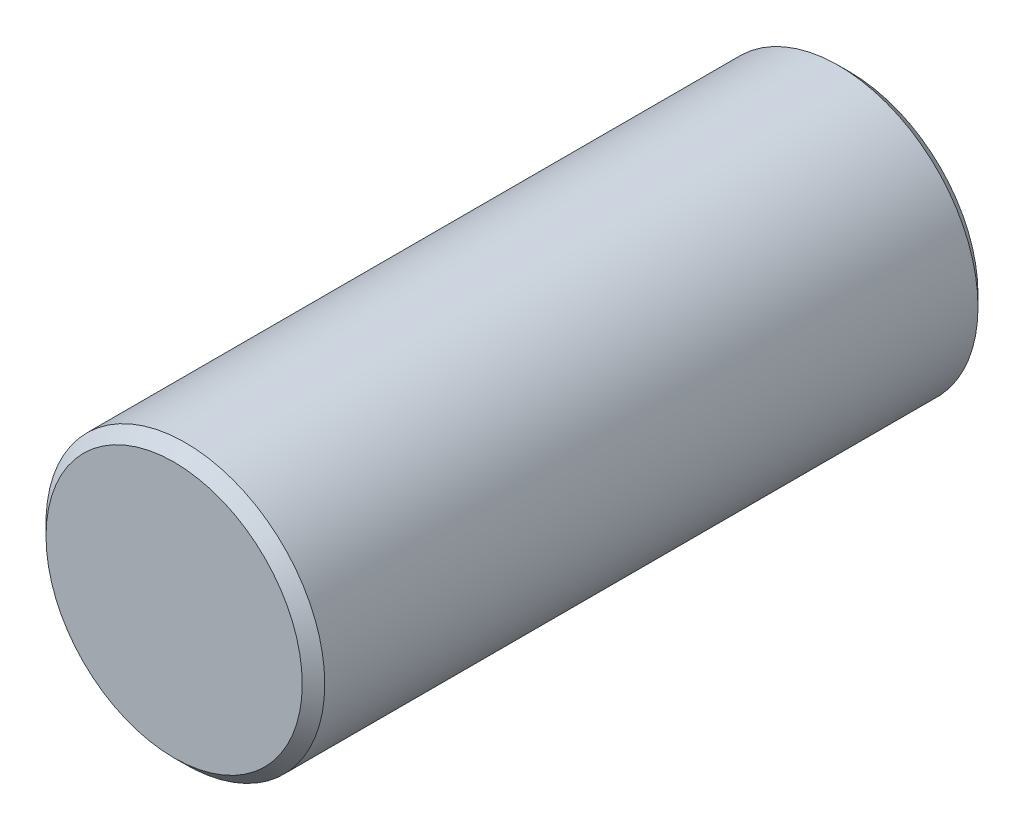
SolidWorks part; units mm, degrees
ref_plane "정면" through (0, 0, 0) normal (0, 0, 1) x (1, 0, 0)
ref_plane "윗면" through (0, 0, 0) normal (0, 1, 0) x (1, 0, 0)
ref_plane "우측면" through (0, 0, 0) normal (1, 0, 0) x (0, 0, -1)
sketch "스케치1" plane through (0, 0, 0) normal (0, 0, 1) x (1, 0, 0)
  circle A0 centre (0, 0) radius 2.475
  dimension "D1" = 4.95
extrude "보스-돌출1" add sketch "스케치1" along normal blind 12 contours A0
chamfer "모따기1" distance 0.2 angle 45 2 edges at (2.475, 0, 0) (2.475, 0, 12)
